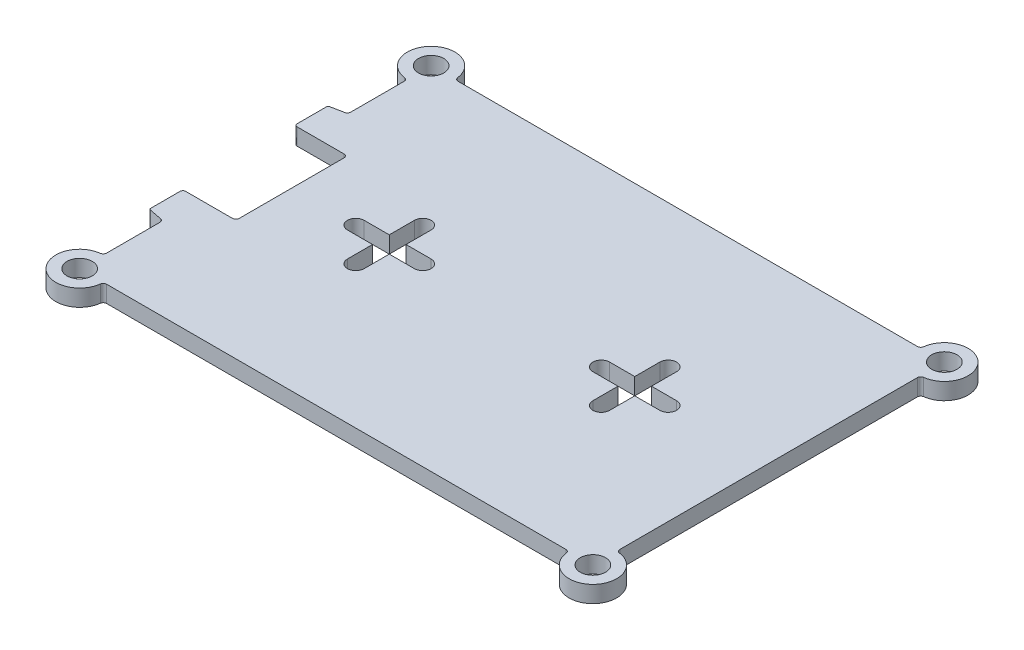
SolidWorks part; units mm, degrees
material "Balsa"
ref_plane "Front Plane" through (0, 0, 0) normal (0, 0, 1) x (1, 0, 0)
ref_plane "Top Plane" through (0, 0, 0) normal (0, 1, 0) x (1, 0, 0)
ref_plane "Right Plane" through (0, 0, 0) normal (1, 0, 0) x (0, 0, -1)
sketch "Sketch1" plane through (0, 0, 0) normal (0, 1, 0) x (1, 0, 0)
  line L0 (46, 0) -> (46, -63) construction
  line L5 (0, -4.265) -> (0, -58.735)
  line L6 (3.2, -3.25) -> (88.8, -3.25) construction
  line L7 (3.2, -3.25) -> (3.2, -59.75) construction
  line L8 (3.2, -59.75) -> (88.8, -59.75) construction
  line L9 (88.8, -3.25) -> (88.8, -59.75) construction
  line L10 (3.2, -3.25) -> (88.8, -59.75) construction
  line L11 (3.2, -59.75) -> (88.8, -3.25) construction
  line L12 (4.265, 0) -> (87.735, 0)
  line L14 (92, -4.265) -> (92, -58.735)
  line L18 (4.265, -63) -> (87.735, -63)
  circle A0 centre (0, 0) radius 2.265
  circle A1 centre (92, 0) radius 2.265
  circle A2 centre (92, -63) radius 2.265
  circle A3 centre (0, -63) radius 2.265
  arc A4 (4.265, 0) -> (0, -4.265) centre (0, 0) ccw
  arc A5 (92, -4.265) -> (87.735, 0) centre (92, 0) ccw
  arc A6 (87.735, -63) -> (92, -58.735) centre (92, -63) ccw
  arc A7 (0, -58.735) -> (4.265, -63) centre (0, -63) ccw
  point P7 (46, -31.5)
  dimension "D5" = 4.53
  dimension "D6" = 2
  dimension "D1" = 92
  dimension "D2" = 63
  dimension "D3" = 85.6
  dimension "D4" = 56.5
extrude "Boss-Extrude1" add sketch "Sketch1" along normal blind 3
sketch "Sketch6" plane through (0, 3, 0) normal (0, 1, 0) x (1, 0, 0)
  line L0 (46, 0) -> (46, -63) construction
  line L1 (87.735, 0) -> (4.265, 0) construction
  line L2 (4.265, -63) -> (87.735, -63) construction
  line L3 (24, -31.5) -> (68, -31.5) construction
  line L4 (18, -31.5) -> (30, -31.5) construction
  line L5 (18, -30) -> (22.5, -30)
  line L6 (18, -33) -> (22.5, -33)
  line L7 (24, -37.5) -> (24, -25.5) construction
  line L8 (22.5, -37.5) -> (22.5, -33)
  line L9 (25.5, -37.5) -> (25.5, -33)
  line L10 (25.5, -30) -> (30, -30)
  line L11 (25.5, -30) -> (25.5, -25.5)
  line L12 (25.5, -33) -> (30, -33)
  line L13 (22.5, -30) -> (22.5, -25.5)
  line L14 (74, -30) -> (69.5, -30)
  line L15 (74, -33) -> (69.5, -33)
  line L16 (69.5, -37.5) -> (69.5, -33)
  line L17 (66.5, -37.5) -> (66.5, -33)
  line L18 (66.5, -33) -> (62, -33)
  line L19 (66.5, -30) -> (62, -30)
  line L20 (66.5, -30) -> (66.5, -25.5)
  line L21 (69.5, -30) -> (69.5, -25.5)
  arc A0 (18, -30) -> (18, -33) centre (18, -31.5) ccw
  arc A1 (30, -33) -> (30, -30) centre (30, -31.5) ccw
  arc A2 (22.5, -37.5) -> (25.5, -37.5) centre (24, -37.5) ccw
  arc A3 (25.5, -25.5) -> (22.5, -25.5) centre (24, -25.5) ccw
  arc A4 (74, -30) -> (74, -33) centre (74, -31.5) cw
  arc A5 (69.5, -37.5) -> (66.5, -37.5) centre (68, -37.5) cw
  arc A6 (62, -33) -> (62, -30) centre (62, -31.5) cw
  arc A7 (66.5, -25.5) -> (69.5, -25.5) centre (68, -25.5) cw
  point P9 (46, -31.5)
  point P11 (24, -31.5)
  point P18 (24, -31.5)
  dimension "D1" = 44
  dimension "D2" = 3
  dimension "D3" = 12
  dimension "D4" = 12
  dimension "D5" = 3
extrude "Cut-Extrude3" cut sketch "Sketch6" against normal blind 3
sketch "Sketch8" plane through (0, 3, 0) normal (0, 1, 0) x (1, 0, 0)
  line L0 (16.5, -31.5) -> (6.5, -31.5) construction
  line L1 (0, -4.265) -> (0, -58.735) construction
  line L2 (0, -21.5) -> (6.5, -21.5)
  line L3 (0, -21.5) -> (0, -41.5)
  line L4 (0, -41.5) -> (6.5, -41.5)
  line L5 (6.5, -21.5) -> (6.5, -41.5)
  arc A0 (18, -30) -> (18, -33) centre (18, -31.5) ccw construction
  point P12 (6.5, -31.5)
  dimension "D1" = 10
  dimension "D2" = 20
extrude "Cut-Extrude4" cut sketch "Sketch8" against normal blind 3
sketch "Sketch9" plane through (0, 3, 0) normal (0, 1, 0) x (1, 0, 0)
  line L0 (0, -4.265) -> (0, -21.5) construction
  line L1 (0, -21.5) -> (-2.5, -21.5)
  line L2 (0, -21.5) -> (0, -14.9015)
  line L4 (-3, -21) -> (-3, -15.7461)
  line L5 (0, -14.9015) -> (-2.7587, -15.4519)
  line L6 (6.5, -31.5) -> (-14.5049, -31.5) construction
  line L7 (6.5, -41.5) -> (6.5, -21.5) construction
  line L8 (0, -41.5) -> (0, -48.0985)
  line L9 (0, -41.5) -> (-2.5, -41.5)
  line L10 (-3, -42) -> (-3, -47.2539)
  line L11 (0, -48.0985) -> (-2.7587, -47.5481)
  arc A0 (-3, -21) -> (-2.5, -21.5) centre (-2.5, -21) ccw
  arc A1 (-3, -15.7461) -> (-2.7587, -15.4519) centre (-2.7, -15.7461) cw
  arc A2 (-3, -42) -> (-2.5, -41.5) centre (-2.5, -42) cw
  arc A3 (-3, -47.2539) -> (-2.7587, -47.5481) centre (-2.7, -47.2539) ccw
  point P7 (-3, -21.5)
  point P12 (-3, -15.5)
  dimension "D3" = 0.5
  dimension "D4" = 0.3
  dimension "D1" = 3
  dimension "D2" = 6
extrude "Boss-Extrude4" add sketch "Sketch9" against normal blind 3
fillet "Fillet1" radius 0.6 12 edges at (87.735, 1.5, 0) (92, 1.5, 4.265) (92, 1.5, 58.735) (87.735, 1.5, 63) (4.265, 1.5, 63) (0, 1.5, 58.735) (0, 1.5, 48.0985) (6.5, 1.5, 41.5) (0, 1.5, 14.9015) (0, 1.5, 4.265) (4.265, 1.5, 0) (6.5, 1.5, 21.5)
